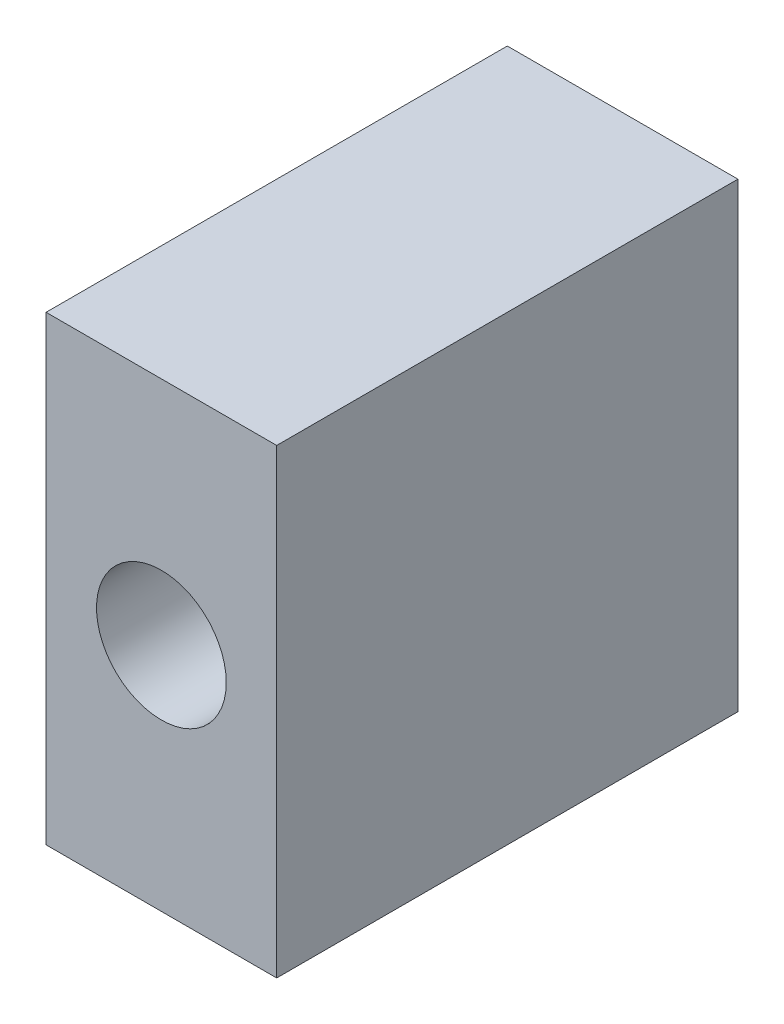
SolidWorks part; units mm, degrees
ref_plane "Front Plane" through (0, 0, 0) normal (0, 0, 1) x (1, 0, 0)
ref_plane "Top Plane" through (0, 0, 0) normal (0, 1, 0) x (1, 0, 0)
ref_plane "Right Plane" through (0, 0, 0) normal (1, 0, 0) x (0, 0, -1)
sketch "Sketch1" plane through (0, 0, 0) normal (0, 0, 1) x (1, 0, 0)
  line L1 (-2, 4) -> (2, 4)
  line L2 (-2, 4) -> (-2, -4)
  line L3 (-2, -4) -> (2, -4)
  line L4 (2, 4) -> (2, -4)
  circle A0 centre (0, 0) radius 1.125
  point P7 (0, 4)
  point P9 (0, 0)
  point P10 (2, 0)
  point P11 (0, 0)
  dimension "D1" = 2.25
  dimension "D2" = 8
  dimension "D3" = 4
extrude "Boss-Extrude1" add sketch "Sketch1" along normal blind 8
